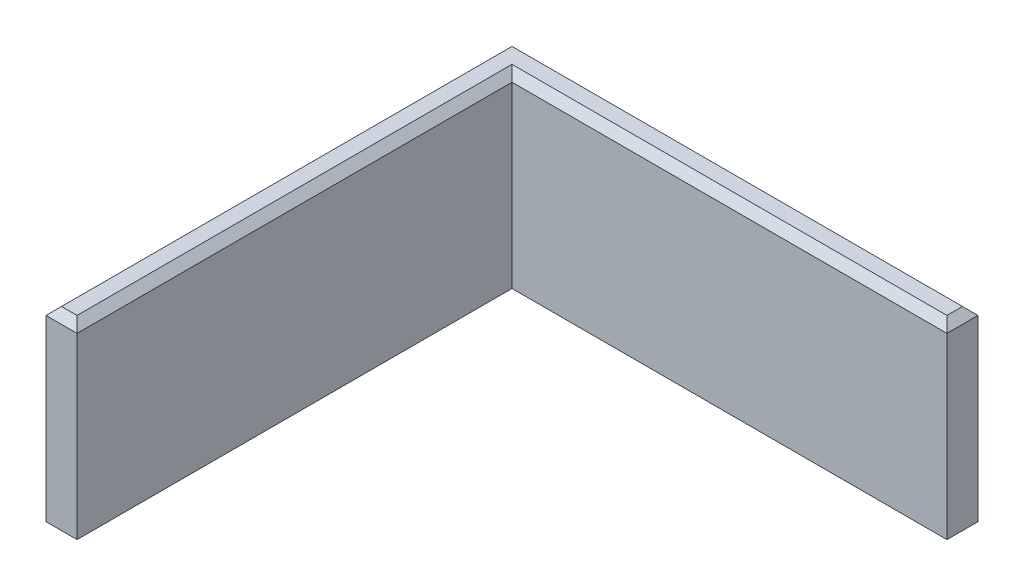
SolidWorks part; units mm, degrees
ref_plane "Front Plane" through (0, 0, 0) normal (0, 0, 1) x (1, 0, 0)
ref_plane "Top Plane" through (0, 0, 0) normal (0, 1, 0) x (1, 0, 0)
ref_plane "Right Plane" through (0, 0, 0) normal (1, 0, 0) x (0, 0, -1)
sketch "Sketch1" plane through (0, 0, 0) normal (0, 1, 0) x (1, 0, 0)
  line L0 (-4, 0) -> (0, 0) construction
  line L1 (0, 0) -> (-4, 0) construction
  line L2 (0, 0) -> (0, -56)
  line L3 (0, -56) -> (-4, -56)
  line L4 (-4, 0) -> (-4, -56)
  line L5 (0, 0) -> (56, 0)
  line L6 (-4, 0) -> (-4, 4)
  line L7 (-4, 4) -> (56, 4)
  line L8 (56, 0) -> (56, 4)
  dimension "D1" = 4
  dimension "D2" = 4
  dimension "D3" = 60
  dimension "D4" = 60
extrude "Boss-Extrude1" add sketch "Sketch1" along normal blind 25
chamfer "Chamfer1" distance 1 angle 45 12 edges at (-2, 25, 56) (0, 25, 28) (28, 25, 0) (56, 25, -2) (-4, 25, 26) (26, 25, -4) (26, 0, -4) (56, 0, -2) (28, 0, 0) (-4, 0, 26) (-2, 0, 56) (0, 0, 28)
fillet "Fillet1" radius 2 1 edges at (-4, 12.5, -4)
